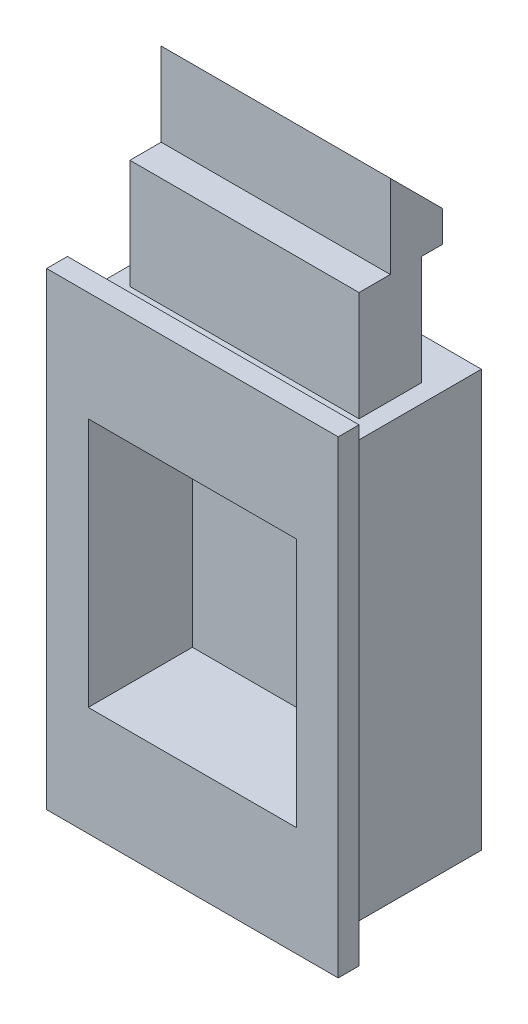
SolidWorks part; units mm, degrees
ref_plane "前视基准面" through (0, 0, 0) normal (0, 0, 1) x (1, 0, 0)
ref_plane "上视基准面" through (0, 0, 0) normal (0, 1, 0) x (1, 0, 0)
ref_plane "右视基准面" through (0, 0, 0) normal (1, 0, 0) x (0, 0, -1)
sketch "草图1" plane through (0, 0, 0) normal (0, 0, 1) x (1, 0, 0)
  line L1 (14, -22.5) -> (-14, -22.5)
  line L2 (14, -22.5) -> (14, 22.5)
  line L3 (14, 22.5) -> (-14, 22.5)
  line L4 (-14, -22.5) -> (-14, 22.5)
  line L5 (14, -22.5) -> (-14, 22.5) construction
  line L6 (14, 22.5) -> (-14, -22.5) construction
  point P0 (0, 0)
  dimension "D1" = 28
  dimension "D2" = 45
extrude "凸台-拉伸1" add sketch "草图1" along normal blind 2
sketch "草图2" plane through (0, 0, 0) normal (0, 0, -1) x (-1, 0, 0)
  line L1 (-12.75, 20) -> (12.75, 20)
  line L2 (-12.75, 20) -> (-12.75, -20)
  line L3 (-12.75, -20) -> (12.75, -20)
  line L4 (12.75, 20) -> (12.75, -20)
  line L5 (-12.75, 20) -> (12.75, -20) construction
  line L6 (-12.75, -20) -> (12.75, 20) construction
  point P0 (0, 0)
  dimension "D1" = 25.5
  dimension "D2" = 40
extrude "凸台-拉伸2" add sketch "草图2" along normal blind 13
sketch "草图3" plane through (0, 0, 0) normal (1, 0, 0) x (0, 0, -1)
  line L0 (13, 20) -> (0, 20) construction
  line L1 (3, 20) -> (9, 20)
  line L2 (3, 20) -> (3, 30.5)
  line L3 (3, 30.5) -> (6, 30.5)
  line L4 (9, 20) -> (9, 30.5)
  line L5 (-2, 22.5) -> (0, 22.5) construction
  line L6 (6, 30.5) -> (6, 38.5)
  line L7 (6, 38.5) -> (11, 33.5)
  line L8 (11, 33.5) -> (11, 30.5)
  line L9 (11, 30.5) -> (9, 30.5)
  line L10 (0, -22.5) -> (0, 22.5) construction
  dimension "D1" = 8
  dimension "D2" = 6
  dimension "D3" = 8
  dimension "D4" = 3
  dimension "D5" = 3
  dimension "D6" = 8
  dimension "D7" = 2
extrude "凸台-拉伸3" add sketch "草图3" along normal mid plane 22
sketch "草图4" plane through (0, 0, 2) normal (0, 0, 1) x (1, 0, 0)
  line L1 (-10, 12) -> (10, 12)
  line L2 (-10, 12) -> (-10, -12)
  line L3 (-10, -12) -> (10, -12)
  line L4 (10, 12) -> (10, -12)
  line L5 (-10, 12) -> (10, -12) construction
  line L6 (-10, -12) -> (10, 12) construction
  point P0 (0, 0)
  dimension "D1" = 20
  dimension "D2" = 24
extrude "切除-拉伸1" cut sketch "草图4" against normal blind 10
